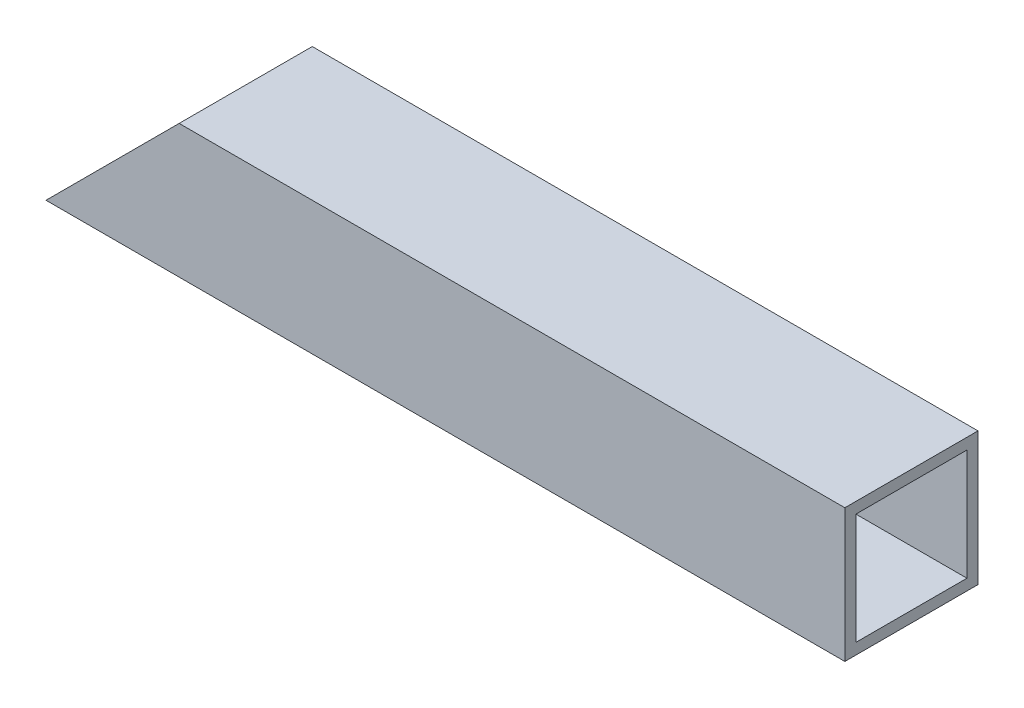
SolidWorks part; units mm, degrees
ref_plane "Alzado" through (0, 0, 0) normal (0, 0, 1) x (1, 0, 0)
ref_plane "Planta" through (0, 0, 0) normal (0, 1, 0) x (1, 0, 0)
ref_plane "Vista lateral" through (0, 0, 0) normal (1, 0, 0) x (0, 0, -1)
sketch "Croquis1" plane through (0, 0, 0) normal (0, 0, 1) x (1, 0, 0)
  line L0 (0, 0) -> (152.4, 0)
  dimension "D1" = 152.4
other "Al tube (square) 1 SQ X .083 WALL(1)"
ref_plane "Plano1" through (0, 0, 0) normal (1, 0, 0) x (0, 1, 0)
sketch "Sketch1" plane through (0, 0, 0) normal (1, 0, 0) x (0, 1, 0)
  line L0 (-10.5918, -10.5918) -> (-10.5918, 10.5918)
  line L1 (10.5918, 10.5918) -> (-10.5918, 10.5918)
  line L2 (10.5918, 10.5918) -> (10.5918, -10.5918)
  line L3 (-10.5918, -10.5918) -> (10.5918, -10.5918)
  line L4 (-12.7, -12.7) -> (12.7, -12.7)
  line L5 (-12.7, -12.7) -> (-12.7, 12.7)
  line L6 (12.7, 12.7) -> (-12.7, 12.7)
  line L7 (12.7, 12.7) -> (12.7, -12.7)
  line L8 (0, -10.5918) -> (0, -12.7) construction
  line L9 (0, -10.5918) -> (0, 10.5918) construction
  line L10 (0, 10.5918) -> (0, 12.7) construction
  line L11 (12.7, 0) -> (10.5918, 0) construction
  line L12 (10.5918, 0) -> (-10.5918, 0) construction
  line L13 (-10.5918, 0) -> (-12.7, 0) construction
  point P14 (0, 0)
  dimension "Thickness" = 2.1082
  dimension "V_leg" = 25.4
  dimension "H_leg" = 25.4
sketch "Croquis3" plane through (0, 0, 12.7) normal (0, 0, 1) x (1, 0, 0)
  line L0 (0, -12.7) -> (25.4, 12.7)
  line L1 (152.4, 12.7) -> (0, 12.7) construction
  line L2 (25.4, 12.7) -> (0, 12.7)
  line L3 (0, 12.7) -> (0, -12.7)
  dimension "D1" = 45
extrude "Cortar-Extruir1" cut sketch "Croquis3" against normal blind 58.928
